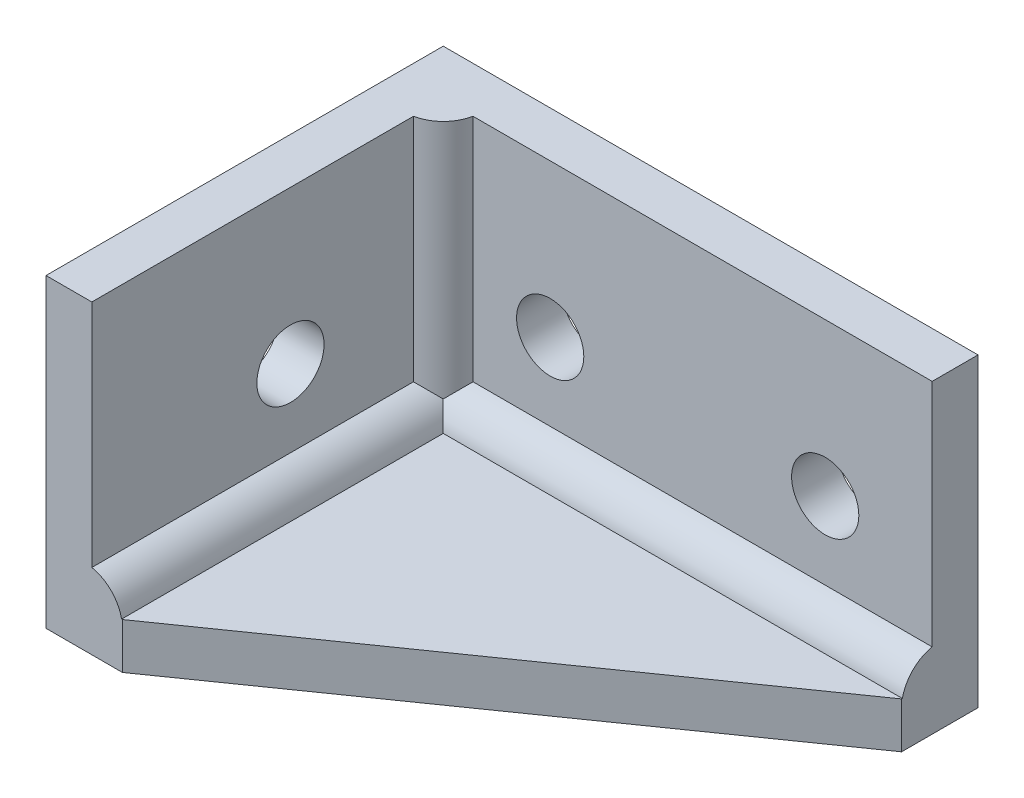
SolidWorks part; units mm, degrees
material "ABS"
ref_plane "Front Plane" through (0, 0, 0) normal (0, 0, 1) x (1, 0, 0)
ref_plane "Top Plane" through (0, 0, 0) normal (0, 1, 0) x (1, 0, 0)
ref_plane "Right Plane" through (0, 0, 0) normal (1, 0, 0) x (0, 0, -1)
sketch "Sketch1" plane through (0, 0, 0) normal (0, 1, 0) x (1, 0, 0)
  line L0 (0, 0) -> (35, 0)
  line L1 (35, 0) -> (35, -5)
  line L2 (35, -5) -> (5, -26)
  line L3 (5, -26) -> (0, -26)
  line L4 (0, -26) -> (0, 0)
  dimension "D1" = 35
  dimension "D2" = 26
  dimension "D3" = 5
  dimension "D4" = 5
extrude "Boss-Extrude1" add sketch "Sketch1" along normal blind 20
sketch "Sketch2" plane through (0, 20, 0) normal (0, 1, 0) x (1, 0, 0)
  line L0 (35, -3) -> (3, -3)
  line L1 (35, 0) -> (35, -5) construction
  line L2 (3, -3) -> (3, -26)
  line L3 (5, -26) -> (0, -26) construction
  line L4 (3, -26) -> (5, -26)
  line L5 (5, -26) -> (35, -5)
  line L6 (35, -5) -> (35, -3)
  line L7 (0, 0) -> (35, 0) construction
  line L9 (0, 0) -> (0, -26) construction
  dimension "D1" = 3
  dimension "D2" = 3
extrude "Cut-Extrude1" cut sketch "Sketch2" against normal blind 17
sketch "Sketch3" plane through (0, 0, 26) normal (0, 0, 1) x (1, 0, 0)
  line L0 (0, 0) -> (5, 0) construction
  line L1 (0, 20) -> (0, 0) construction
  circle A0 centre (2.5, 2.5) radius 2.5
  dimension "D1" = 5
extrude "Boss-Extrude2" add sketch "Sketch3" against normal up to next
sketch "Sketch4" plane through (35, 0, 0) normal (1, 0, 0) x (0, 0, -1)
  line L2 (0, 20) -> (0, 0) construction
  line L3 (-5, 0) -> (0, 0) construction
  circle A0 centre (-2.5, 2.5) radius 2.5
  dimension "D1" = 5
extrude "Boss-Extrude3" add sketch "Sketch4" against normal up to next
sketch "Sketch5" plane through (0, 20, 0) normal (0, 1, 0) x (1, 0, 0)
  line L2 (35, 0) -> (0, 0) construction
  line L3 (0, 0) -> (0, -26) construction
  circle A0 centre (2.5, -2.5) radius 2.5
  dimension "D1" = 5
extrude "Boss-Extrude4" add sketch "Sketch5" against normal up to next
sketch "Sketch6" plane through (0, 0, 3) normal (0, 0, 1) x (1, 0, 0)
  line L2 (35, 4.9495) -> (35, 20) construction
  line L3 (35, 20) -> (4.9495, 20) construction
  circle A0 centre (10, 10) radius 2.2
  circle A1 centre (28, 10) radius 2.2
  dimension "D1" = 4.4
  dimension "D2" = 18
  dimension "D3" = 7
  dimension "D4" = 10
extrude "Cut-Extrude2" cut sketch "Sketch6" against normal through all
sketch "Sketch7" plane through (3, 0, 0) normal (1, 0, 0) x (0, 0, -1)
  line L2 (-26, 4.9495) -> (-26, 20) construction
  line L3 (-4.9495, 20) -> (-26, 20) construction
  circle A0 centre (-13, 10) radius 2.2
  dimension "D1" = 4.4
  dimension "D2" = 10
  dimension "D3" = 13
extrude "Cut-Extrude3" cut sketch "Sketch7" against normal through all
